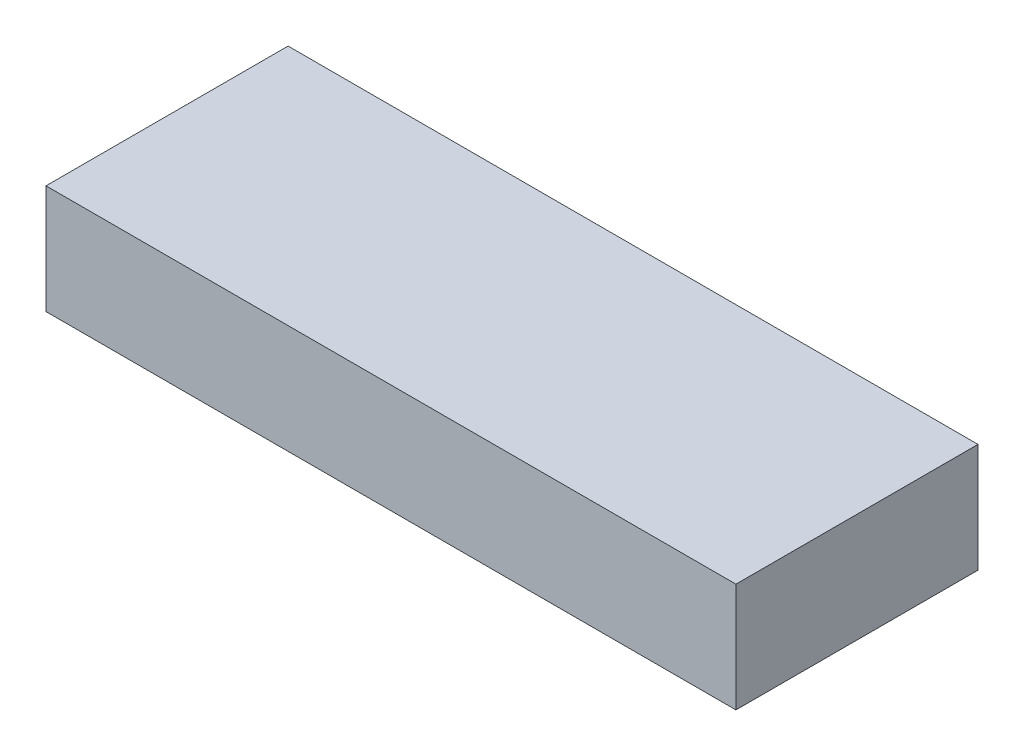
SolidWorks part; units mm, degrees
ref_plane "Front Plane" through (0, 0, 0) normal (0, 0, 1) x (1, 0, 0)
ref_plane "Top Plane" through (0, 0, 0) normal (0, 1, 0) x (1, 0, 0)
ref_plane "Right Plane" through (0, 0, 0) normal (1, 0, 0) x (0, 0, -1)
sketch "Sketch1" plane through (0, 0, 0) normal (0, 1, 0) x (1, 0, 0)
  line L1 (-72.39, 25.4) -> (72.39, 25.4)
  line L2 (-72.39, 25.4) -> (-72.39, -25.4)
  line L3 (-72.39, -25.4) -> (72.39, -25.4)
  line L4 (72.39, 25.4) -> (72.39, -25.4)
  line L5 (-72.39, 25.4) -> (72.39, -25.4) construction
  line L6 (-72.39, -25.4) -> (72.39, 25.4) construction
  point P0 (0, 0)
  dimension "D1" = 50.8
  dimension "D2" = 144.78
extrude "Boss-Extrude1" add sketch "Sketch1" along normal blind 22.86
ref_plane "Plane1" through (0, 11.43, 0) normal (0, -1, 0) x (-1, 0, 0)
